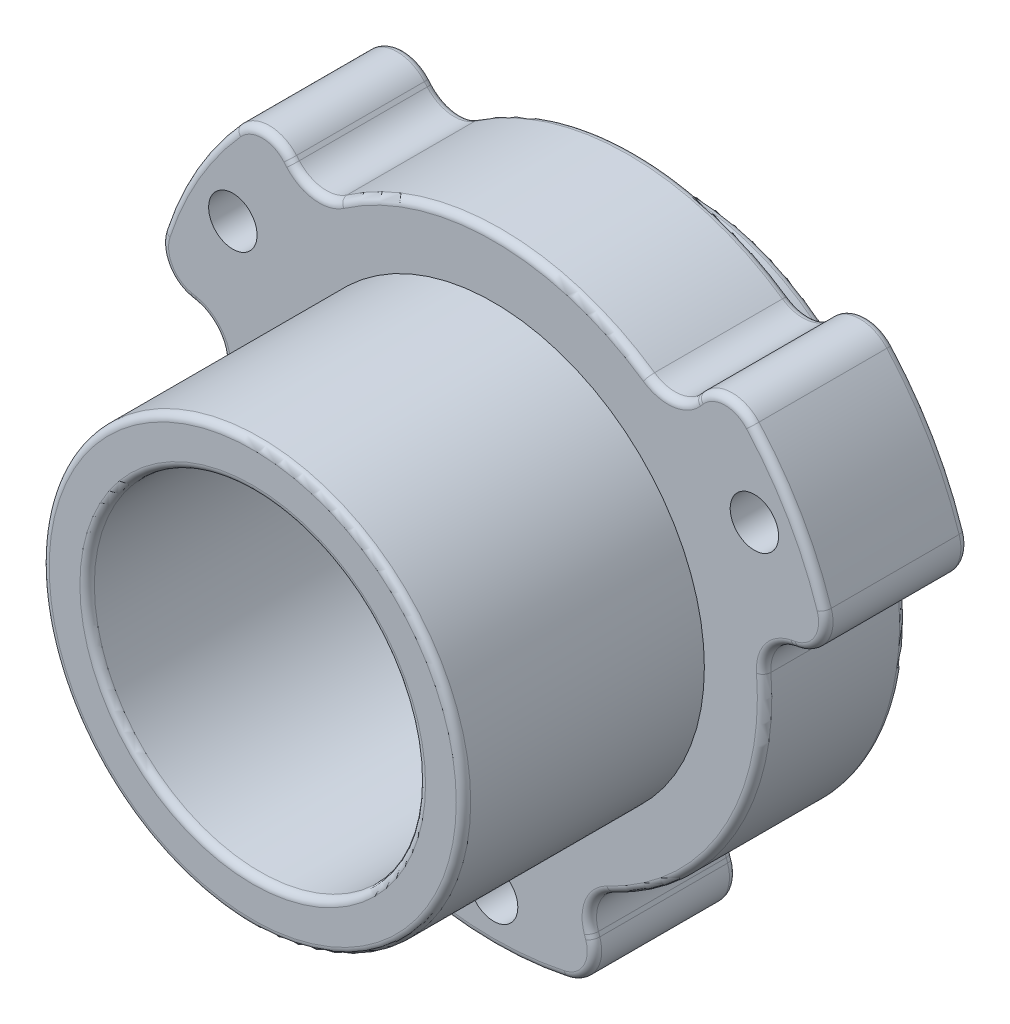
SolidWorks part; units mm, degrees
material "6061 Alloy"
ref_plane "Front Plane" through (0, 0, 0) normal (0, 0, 1) x (1, 0, 0)
ref_plane "Top Plane" through (0, 0, 0) normal (0, 1, 0) x (1, 0, 0)
ref_plane "Right Plane" through (0, 0, 0) normal (1, 0, 0) x (0, 0, -1)
sketch "Sketch2" plane through (0, 0, 0) normal (0, 0, 1) x (1, 0, 0)
  circle A0 centre (0, 0) radius 36.6395
  dimension "D1" = 73.279
extrude "Boss-Extrude1" add sketch "Sketch2" along normal blind 15
sketch "Sketch3" plane through (0, 0, 0) normal (0, 0, 1) x (1, 0, 0)
  circle A0 centre (0, 0) radius 22.225
  dimension "D1" = 44.45
extrude "Boss-Extrude2" add sketch "Sketch3" against normal blind 5.715
sketch "Sketch6" plane through (0, 0, 15) normal (0, 0, 1) x (1, 0, 0)
  circle A0 centre (0, 0) radius 22.225
  dimension "D1" = 44.45
extrude "Boss-Extrude3" add sketch "Sketch6" along normal blind 25.4
sketch "Sketch5" plane through (0, 0, -5.715) normal (0, 0, -1) x (-1, 0, 0)
  circle A0 centre (0, 0) radius 17.4625
  dimension "D1" = 34.925
extrude "Cut-Extrude1" cut sketch "Sketch5" against normal through all
hole_wizard "1/4-20 Tapped Hole1" positions "Sketch9" profile "Sketch8" tap size "1/4-20" standard "ANSI Inch" end condition through all
sketch "Sketch9" plane through (0, 0, 0) normal (0, 0, -1) x (-1, 0, 0)
  circle A0 centre (0, 0) radius 31.75
  point P6 (0, -31.75)
  point P12 (-27.4963, 15.875)
  point P13 (27.4963, 15.875)
  dimension "D1" = 63.5
  dimension "D2" = 3
sketch "Sketch8" plane through (-27.4963, 15.875, 0) normal (1, 0, 0) x (0, 1, 0)
  line L0 (0, 0) -> (0, 40.4)
  line L1 (0, 40.4) -> (2.5527, 40.4)
  line L2 (2.5527, 40.4) -> (2.5527, 0)
  line L5 (2.5527, 0) -> (0, 0)
  line L11 (0, -6.35) -> (0, 107.95) construction
  dimension "Thru Tap Drill Dia." = 5.1054
  dimension "Thru Tap Drill Depth" = 40.4
cosmetic thread "Hole Thread1" parameters "D2"=6.35
cosmetic thread "Hole Thread2" parameters "D2"=6.35
cosmetic thread "Hole Thread3" parameters "D2"=6.35
sketch "Sketch10" plane through (0, 0, 15) normal (0, 0, 1) x (1, 0, 0)
  line L0 (-18.8734, 21.4552) -> (-24.1999, 27.5103)
  line L1 (18.8734, 21.4552) -> (24.1999, 27.5103)
  line L2 (28.0174, 5.6173) -> (35.9246, 7.2026)
  line L3 (9.144, -27.0725) -> (11.7246, -34.7129)
  line L4 (-9.144, -27.0725) -> (-11.7246, -34.7129)
  line L5 (-28.0174, 5.6173) -> (-35.9246, 7.2026)
  circle A0 centre (0, 0) radius 36.6395 construction
  arc A1 (24.1999, 27.5103) -> (-24.1999, 27.5103) centre (0, 0) ccw
  arc A2 (18.8734, 21.4552) -> (-18.8734, 21.4552) centre (0, 0) ccw
  circle A3 centre (-27.4963, 15.875) radius 2.5527 construction
  circle A4 centre (27.4963, 15.875) radius 2.5527 construction
  arc A5 (9.144, -27.0725) -> (28.0174, 5.6173) centre (0, 0) ccw
  arc A6 (11.7246, -34.7129) -> (35.9246, 7.2026) centre (0, 0) ccw
  arc A7 (-28.0174, 5.6173) -> (-9.144, -27.0725) centre (0, 0) ccw
  arc A8 (-35.9246, 7.2026) -> (-11.7246, -34.7129) centre (0, 0) ccw
  point P21 (0, 0)
  dimension "D1" = 57.15
  dimension "D2" = 10.16
  dimension "D3" = 10.16
  dimension "D4" = 3
extrude "Cut-Extrude2" cut sketch "Sketch10" against normal through all
fillet "Fillet1" radius 3.81 12 edges at (18.8734, 21.4552, 7.5) (24.1999, 27.5103, 7.5) (-18.8734, 21.4552, 7.5) (-24.1999, 27.5103, 7.5) (-35.9246, 7.2026, 7.5) (-28.0174, 5.6173, 7.5) (35.9246, 7.2026, 7.5) (28.0174, 5.6173, 7.5) (11.7246, -34.7129, 7.5) (-11.7246, -34.7129, 7.5) (-9.144, -27.0725, 7.5) (9.144, -27.0725, 7.5)
fillet "Fillet2" radius 0.762 52 edges at (29.2404, 4.8815, 15) (31.752, 6.366, 15) (34.5109, 8.2217, 15) (31.7307, 18.3198, 15) (24.3757, 25.7765, 15) (21.3892, 24.315, 15) (18.8477, 22.8822, 15) (0, 28.575, 15) (-18.8477, 22.8822, 15) (-21.3892, 24.315, 15) (-24.3757, 25.7765, 15) (-31.7307, 18.3197, 15) (-34.5109, 8.2217, 15) (-31.752, 6.366, 15) (-29.2404, 4.8815, 15) (-24.7467, -14.2875, 15) (-10.3927, -27.7637, 15) (-10.3628, -30.6811, 15) (-10.1353, -33.9982, 15) (0, -36.6395, 15) (10.1353, -33.9982, 15) (10.3628, -30.6811, 15) (10.3927, -27.7637, 15) (29.2404, 4.8815, 0) (31.752, 6.366, 0) (34.5109, 8.2217, 0) (31.7307, 18.3198, 0) (24.3757, 25.7765, 0) (21.3892, 24.315, 0) (18.8477, 22.8822, 0) (0, 28.575, 0) (-18.8477, 22.8822, 0) (-21.3892, 24.315, 0) (-24.3757, 25.7765, 0) (-31.7307, 18.3197, 0) (-34.5109, 8.2217, 0) (-31.752, 6.366, 0) (-29.2404, 4.8815, 0) (-24.7467, -14.2875, 0) (-10.3927, -27.7637, 0) (-10.3628, -30.6811, 0) (-10.1353, -33.9982, 0) (0, -36.6395, 0) (10.1353, -33.9982, 0) (10.3628, -30.6811, 0) (10.3927, -27.7637, 0) (22.225, 0, -5.715) (-17.4625, 0, -5.715) (-17.4625, 0, 40.4) (22.225, 0, 40.4) (24.7467, -14.2875, 15) (24.7467, -14.2875, 0)
